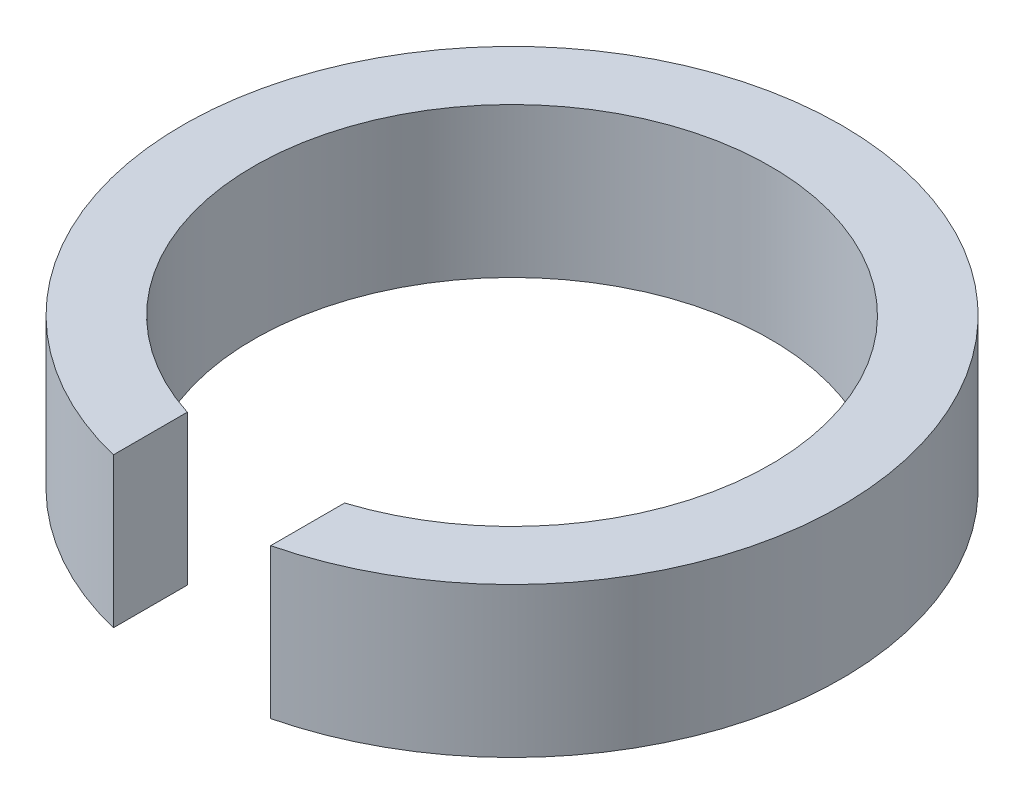
SolidWorks part; units mm, degrees
ref_plane "Front Plane" through (0, 0, 0) normal (0, 0, 1) x (1, 0, 0)
ref_plane "Top Plane" through (0, 0, 0) normal (0, 1, 0) x (1, 0, 0)
ref_plane "Right Plane" through (0, 0, 0) normal (1, 0, 0) x (0, 0, -1)
sketch "Sketch1" plane through (0, 0, 0) normal (0, 1, 0) x (1, 0, 0)
  line L0 (0, 0) -> (0, -3.45) construction
  line L1 (0, -3.45) -> (0, -4.4) construction
  line L3 (-1.05, -3.0135) -> (1.05, -3.0135)
  line L4 (-1.05, -3.0135) -> (-1.05, -4.8365)
  line L5 (-1.05, -4.8365) -> (1.05, -4.8365)
  line L6 (1.05, -3.0135) -> (1.05, -4.8365)
  line L7 (-1.05, -3.0135) -> (1.05, -4.8365) construction
  line L8 (-1.05, -4.8365) -> (1.05, -3.0135) construction
  circle A0 centre (0, 0) radius 3.45
  circle A1 centre (0, 0) radius 4.4
  point P4 (0, -3.925)
  dimension "D1" = 8.8
  dimension "D2" = 6.9
  dimension "D3" = 0.95
  dimension "D4" = 2.1
extrude "Boss-Extrude1" add sketch "Sketch1" along normal blind 2 contours L6 A1 L4 A0
